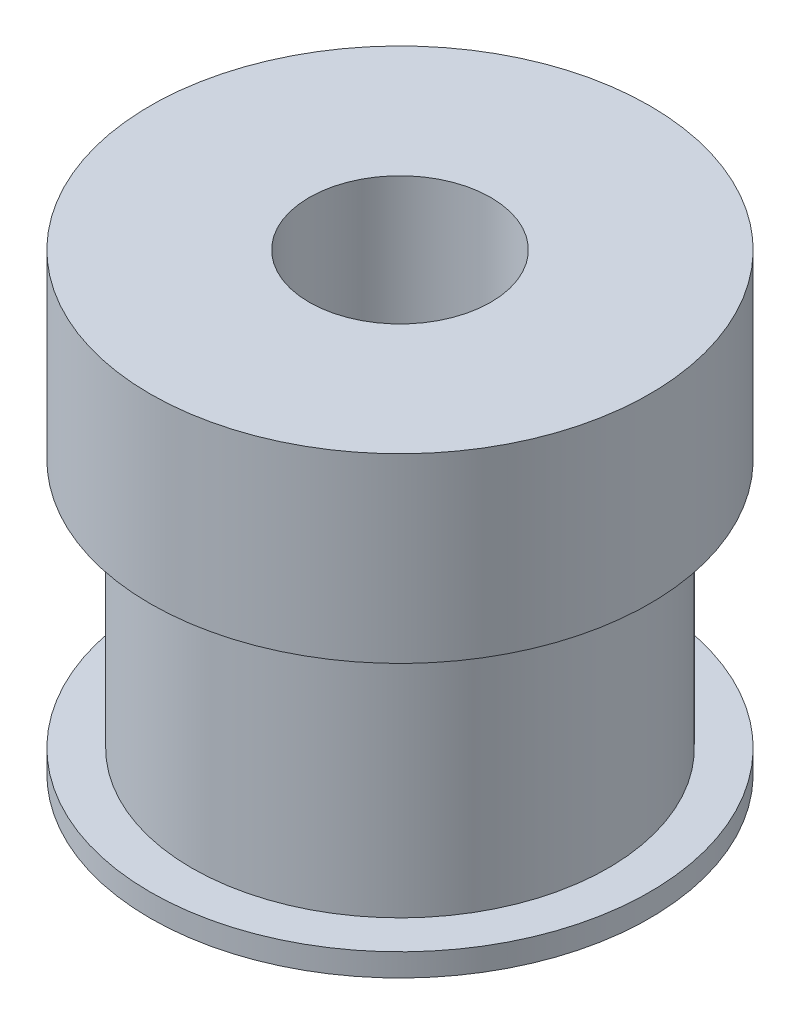
SolidWorks part; units mm, degrees
ref_plane "Спереди" through (0, 0, 0) normal (0, 0, 1) x (1, 0, 0)
ref_plane "Сверху" through (0, 0, 0) normal (0, 1, 0) x (1, 0, 0)
ref_plane "Справа" through (0, 0, 0) normal (1, 0, 0) x (0, 0, -1)
sketch "Эскиз1" plane through (0, 0, 0) normal (0, 1, 0) x (1, 0, 0)
  circle A0 centre (0, 0) radius 11
  dimension "D1" = 22
extrude "Бобышка-Вытянуть1" add sketch "Эскиз1" along normal blind 1
sketch "Эскиз2" plane through (0, 1, 0) normal (0, 1, 0) x (1, 0, 0)
  circle A0 centre (0, 0) radius 9.17
  dimension "D1" = 18.34
extrude "Бобышка-Вытянуть2" add sketch "Эскиз2" along normal blind 11
sketch "Эскиз3" plane through (0, 12, 0) normal (0, 1, 0) x (1, 0, 0)
  circle A0 centre (0, 0) radius 11
  dimension "D1" = 22
extrude "Бобышка-Вытянуть3" add sketch "Эскиз3" along normal blind 8
sketch "Эскиз4" plane through (0, 20, 0) normal (0, 1, 0) x (1, 0, 0)
  circle A0 centre (0, 0) radius 4
  dimension "D1" = 8
extrude "Вырез-Вытянуть1" cut sketch "Эскиз4" against normal through all
